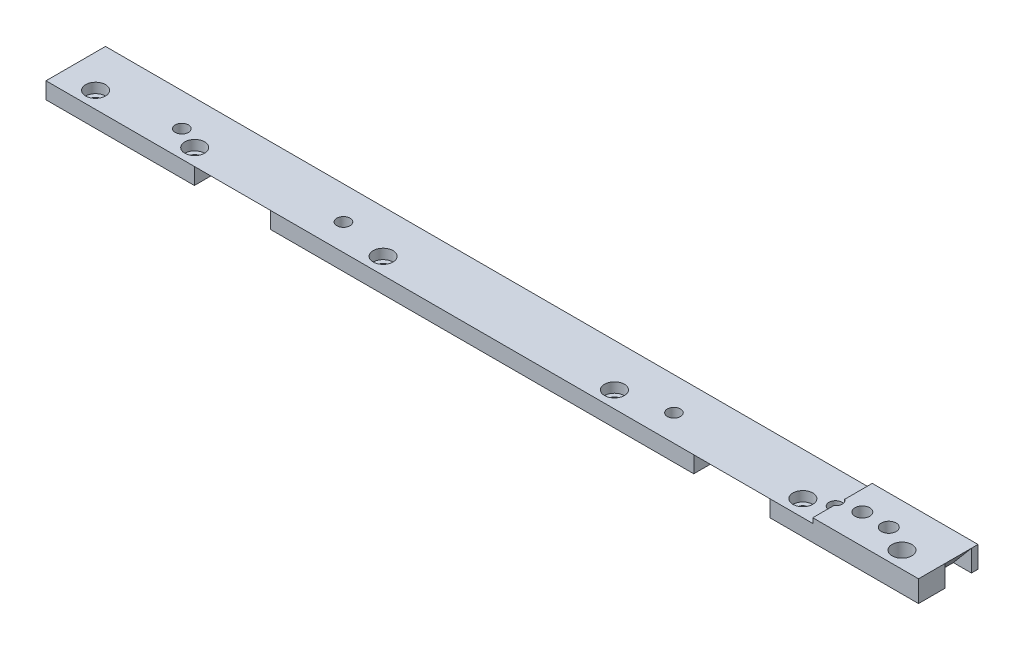
SolidWorks part; units mm, degrees
material "ABS"
ref_plane "Ebene vorne" through (0, 0, 0) normal (0, 0, 1) x (1, 0, 0)
ref_plane "Ebene oben" through (0, 0, 0) normal (0, 1, 0) x (1, 0, 0)
ref_plane "Ebene rechts" through (0, 0, 0) normal (1, 0, 0) x (0, 0, -1)
sketch "Skizze1" plane through (0, 0, 0) normal (0, 1, 0) x (1, 0, 0)
  line L0 (132, 18) -> (132, 0) construction
  line L1 (0, 0) -> (264, 0)
  line L2 (0, 0) -> (0, 18)
  line L3 (0, 18) -> (264, 18)
  line L4 (264, 0) -> (264, 18)
  line L5 (0, 9) -> (26, 9) construction
  line L6 (97, 5) -> (167, 5) construction
  line L7 (82, 8) -> (182, 8) construction
  circle A0 centre (10, 5) radius 1.65
  circle A1 centre (40, 5) radius 1.65
  circle A2 centre (26, 9) radius 2.25
  circle A3 centre (18, 9) radius 2.25
  circle A4 centre (224, 5) radius 1.65
  circle A5 centre (254, 5) radius 1.65
  circle A6 centre (246, 9) radius 2.25
  circle A7 centre (238, 9) radius 2.25
  circle A8 centre (230.9, 8) radius 2
  circle A9 centre (33.1, 8) radius 2
  circle A10 centre (97, 5) radius 1.65
  circle A11 centre (167, 5) radius 1.65
  circle A12 centre (82, 8) radius 2
  circle A13 centre (182, 8) radius 2
  point P32 (132, 5)
  point P37 (132, 8)
  dimension "D4" = 5
  dimension "D5" = 3.3
  dimension "D7" = 18
  dimension "D8" = 8
  dimension "D9" = 4.5
  dimension "D11" = 4.5
  dimension "D12" = 70
  dimension "D13" = 100
  dimension "D16" = 10
  dimension "D17" = 4
  dimension "D1" = 264
  dimension "D2" = 18
  dimension "D3" = 10
  dimension "D6" = 40
  dimension "D10" = 9
  dimension "D15" = 33.1
extrude "Aufsatz-Linear austragen1" add sketch "Skizze1" along normal blind 5
sketch "Skizze2" plane through (0, 0, -18) normal (0, 0, -1) x (-1, 0, 0)
  line L0 (0, 0) -> (0, 5)
  line L1 (0, 5) -> (-4.1955, 0)
  line L2 (-264, 0) -> (0, 0) construction
  line L3 (-4.1955, 0) -> (16.3956, 0)
  line L4 (-132, 5) -> (-132, 0) construction
  line L5 (-264, 5) -> (0, 5) construction
  line L6 (-259.8045, 0) -> (-280.3956, 0)
  line L7 (-264, 5) -> (-259.8045, 0)
  line L8 (-264, 0) -> (-264, 5)
  line M1 (-264, 0) -> (0, 0)
  line M2 (0, 0) -> (0, 5)
  line M4 (-264, 5) -> (-264, 0)
  dimension "D1" = 40
extrude "Schnitt-Linear austragen1" cut sketch "Skizze2" against normal blind 8 from offset 2 contours L1 M2 M1 | L7 M4 M1
sketch "Skizze3" plane through (0, 0, 0) normal (-1, 0, 0) x (0, 0, 1)
  line L0 (0, 5) -> (-5, 0)
  line L1 (-8, 0) -> (0, 0) construction
  line L2 (-5, 0) -> (0, 0)
  line L3 (0, 0) -> (0, 5)
  dimension "D1" = 45
extrude "Schnitt-Linear austragen2" cut sketch "Skizze3" against normal blind 23.1 from offset 44.9
sketch "Skizze4" plane through (264, 0, 0) normal (1, 0, 0) x (0, 0, -1)
  line L0 (0, 5) -> (5, 0)
  line L1 (0, 0) -> (8, 0) construction
  line L2 (5, 0) -> (0, 0)
  line L3 (0, 0) -> (0, 5)
  dimension "D1" = 45
extrude "Schnitt-Linear austragen3" cut sketch "Skizze4" against normal blind 23.1 from offset 44.9
sketch "Skizze5" plane through (0, 5, 0) normal (0, 1, 0) x (1, 0, 0)
  circle A0 centre (254, 5) radius 3
  circle A1 centre (224, 5) radius 3
  circle A2 centre (40, 5) radius 3
  circle A3 centre (10, 5) radius 3
  circle A4 centre (97, 5) radius 3
  circle A5 centre (167, 5) radius 3
  dimension "D1" = 6
extrude "Schnitt-Linear austragen4" cut sketch "Skizze5" against normal blind 3
sketch "Skizze7" plane through (0, 5, 0) normal (0, 1, 0) x (1, 0, 0)
  line L0 (219.1, 0) -> (264, 0) construction
  line L1 (264, 18) -> (232, 18)
  line L2 (264, 18) -> (264, 0)
  line L3 (264, 0) -> (232, 0)
  line L4 (232, 18) -> (232, 0)
  line L5 (132, 18) -> (132, 0) construction
  line L6 (264, 18) -> (0, 18) construction
  line L7 (68, 0) -> (196, 0) construction
  circle A0 centre (238, 9) radius 2.25 construction
  circle A1 centre (246, 9) radius 2.25 construction
  circle A2 centre (254, 5) radius 3 construction
  circle A3 centre (238, 9) radius 2.25
  circle A4 centre (246, 9) radius 2.25
  circle A5 centre (254, 5) radius 3
  dimension "D1" = 6
extrude "Aufsatz-Linear austragen3" add sketch "Skizze7" along normal blind 1.5
sketch "Skizze8" plane through (0, 5, 0) normal (0, 1, 0) x (1, 0, 0)
  circle A0 centre (18, 9) radius 2.25 construction
  circle A1 centre (26, 9) radius 2.25 construction
  circle A2 centre (18, 9) radius 2.25
  circle A3 centre (26, 9) radius 2.25
extrude "Aufsatz-Linear austragen4" add sketch "Skizze8" against normal up to surface (5 mm away) up to face at (182, 0, -6)
sketch "Skizze9" plane through (0, 0, -18) normal (0, 0, -1) x (-1, 0, 0)
  line L1 (-264, 6.5) -> (-264, 0)
  line L2 (-264, 0) -> (-258.5459, 0)
  line L3 (-264, 0) -> (0, 0) construction
  line L4 (-258.5459, 0) -> (-264, 6.5)
  line L5 (-264, 5) -> (-259.8045, 0) construction
extrude "Schnitt-Linear austragen6" cut sketch "Skizze9" against normal up to surface (8 mm away) from offset 2 up to face at (263.3008, 3.3333, -8)
sketch "Skizze10" plane through (0, 5, 0) normal (0, 1, 0) x (1, 0, 0)
  circle A0 centre (230.9, 8) radius 2 construction
  circle A1 centre (230.9, 8) radius 2
extrude "Schnitt-Linear austragen7" cut sketch "Skizze10" along normal up to surface (1.5 mm away) up to face at (246, 6.5, -6.75)
